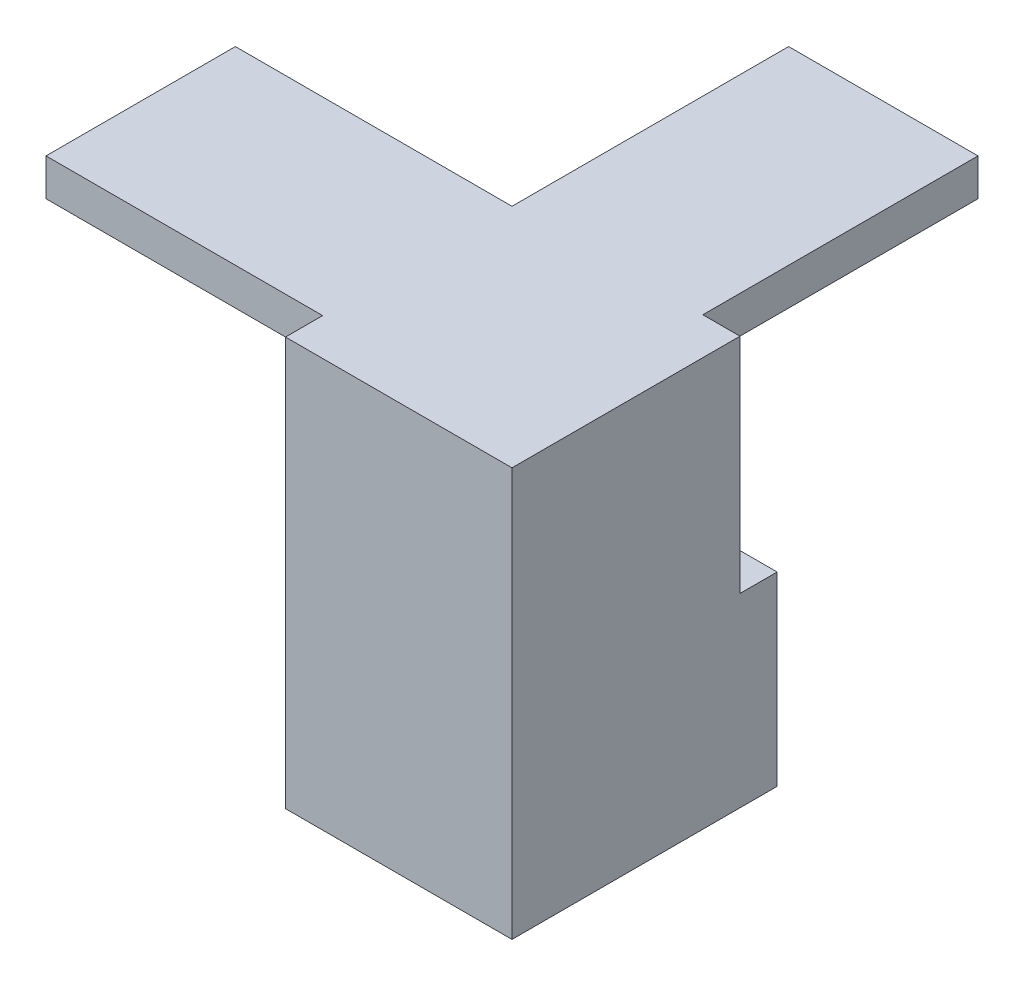
SolidWorks part; units mm, degrees
ref_plane "Front Plane" through (0, 0, 0) normal (0, 0, 1) x (1, 0, 0)
ref_plane "Top Plane" through (0, 0, 0) normal (0, 1, 0) x (1, 0, 0)
ref_plane "Right Plane" through (0, 0, 0) normal (1, 0, 0) x (0, 0, -1)
sketch "Sketch2" plane through (0, 0, 0) normal (0, 1, 0) x (1, 0, 0)
  line L0 (0, 0) -> (0, 50) construction
  line L1 (0, 0) -> (-50, 0) construction
  line L2 (-12.75, 12.75) -> (-12.75, 50)
  line L3 (-12.75, 12.75) -> (-50, 12.75)
  line L4 (12.75, -12.75) -> (12.75, 50)
  line L5 (12.75, -12.75) -> (-50, -12.75)
  line L6 (-50, 12.75) -> (-50, -12.75)
  line L7 (-12.75, 50) -> (12.75, 50)
  dimension "D1" = 12.75
  dimension "D2" = 12.75
extrude "Boss-Extrude1" add sketch "Sketch2" along normal blind 5
sketch "Sketch3" plane through (0, 0, 12.75) normal (0, 0, 1) x (1, 0, 0)
  line L0 (12.75, 0) -> (12.75, -50)
  line L2 (-50, 0) -> (12.75, 0) construction
  line L3 (-12.75, 0) -> (-12.75, -50)
  line L4 (-12.75, -50) -> (12.75, -50)
  line L5 (-12.75, 0) -> (-12.75, 5)
  line L6 (12.75, 0) -> (12.75, 5)
  line L7 (12.75, 5) -> (-12.75, 5)
extrude "Boss-Extrude2" add sketch "Sketch3" along normal blind 5
sketch "Sketch4" plane through (12.75, 0, 0) normal (1, 0, 0) x (0, 0, -1)
  line L0 (-17.75, 5) -> (12.95, 5)
  line L1 (-17.75, 5) -> (50, 5) construction
  line L2 (12.95, 5) -> (12.95, -50)
  line L3 (-17.75, -50) -> (12.95, -50)
  line L4 (-17.75, -50) -> (-17.75, 5)
extrude "Boss-Extrude3" add sketch "Sketch4" along normal blind 5
sketch "Sketch5" plane through (0, 0, -12.95) normal (0, 0, -1) x (-1, 0, 0)
  line L0 (-17.75, -50) -> (17.75, -50)
  line L1 (17.75, -50) -> (17.75, -25)
  line L2 (17.75, -25) -> (-17.75, -25)
  line L3 (-17.75, -50) -> (-17.75, -25)
extrude "Boss-Extrude4" add sketch "Sketch5" along normal blind 5
